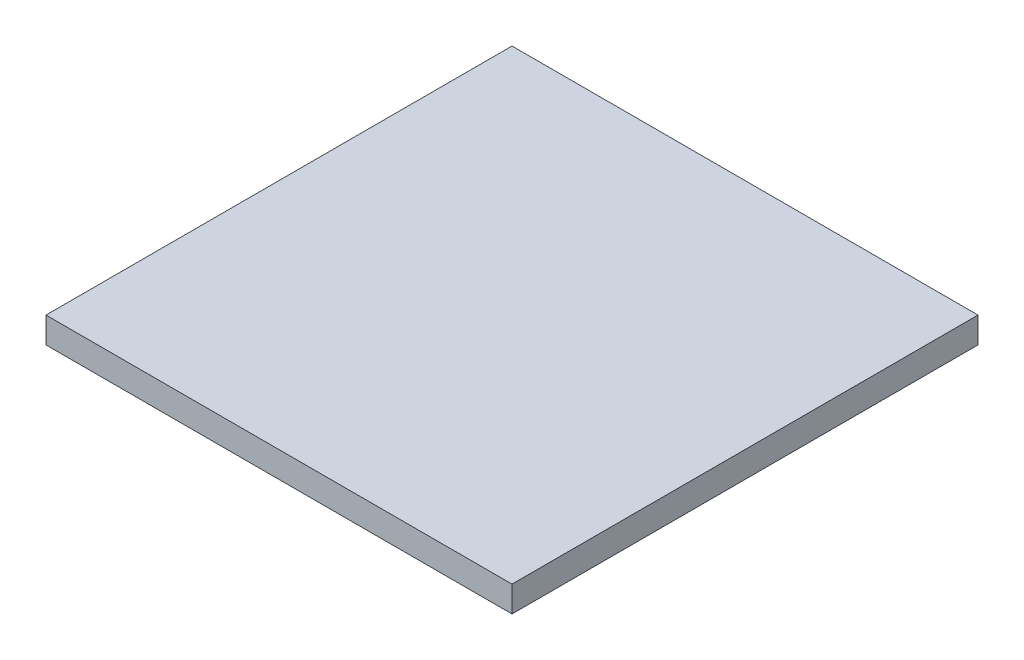
SolidWorks part; units mm, degrees
ref_plane "Front Plane" through (0, 0, 0) normal (0, 0, 1) x (1, 0, 0)
ref_plane "Top Plane" through (0, 0, 0) normal (0, 1, 0) x (1, 0, 0)
ref_plane "Right Plane" through (0, 0, 0) normal (1, 0, 0) x (0, 0, -1)
sketch "Sketch1" plane through (0, 0, 0) normal (0, 1, 0) x (1, 0, 0)
  line L1 (0, 0) -> (180, 0)
  line L2 (0, 0) -> (0, 180)
  line L3 (0, 180) -> (180, 180)
  line L4 (180, 0) -> (180, 180)
  dimension "D1" = 180
  dimension "D2" = 180
extrude "Boss-Extrude1" add sketch "Sketch1" along normal blind 10
